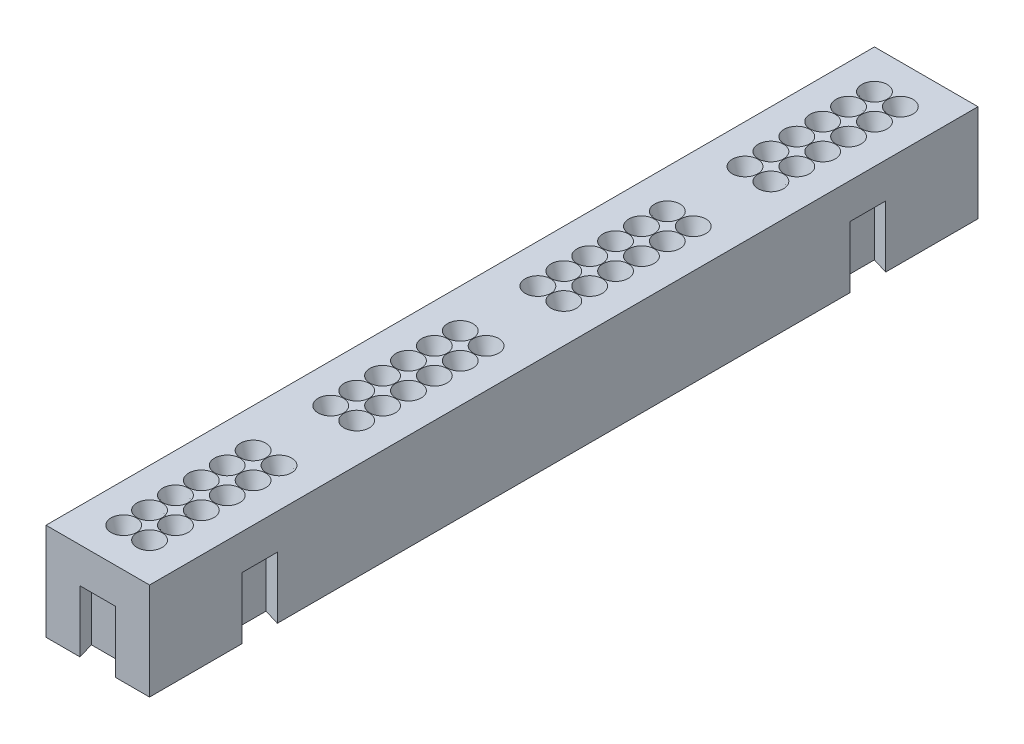
SolidWorks part; units mm, degrees
ref_plane "Front Plane" through (0, 0, 0) normal (0, 0, 1) x (1, 0, 0)
ref_plane "Top Plane" through (0, 0, 0) normal (0, 1, 0) x (1, 0, 0)
ref_plane "Right Plane" through (0, 0, 0) normal (1, 0, 0) x (0, 0, -1)
sketch "Sketch1" plane through (0, 0, 0) normal (0, 1, 0) x (1, 0, 0)
  line L0 (-5.08, -40.64) -> (5.08, 40.64) construction
  line L1 (-5.08, 40.64) -> (5.08, 40.64)
  line L2 (-5.08, 40.64) -> (-5.08, -40.64)
  line L3 (-5.08, -40.64) -> (5.08, -40.64)
  line L4 (5.08, 40.64) -> (5.08, -40.64)
  dimension "D1" = 81.28
  dimension "D2" = 10.16
extrude "Extrude1" add sketch "Sketch1" along normal blind 9.525
sketch "Sketch4" plane through (0, 0, 0) normal (0, -1, 0) x (1, 0, 0)
  line L0 (5.08, -29.845) -> (-5.08, -29.845) construction
  line L1 (5.08, 40.64) -> (5.08, -40.64) construction
  line L2 (-5.08, -40.64) -> (-5.08, 40.64) construction
  line L3 (0, -40.64) -> (0, 40.64) construction
  line L4 (5.08, 29.845) -> (-5.08, 29.845) construction
  line L5 (5.08, -40.64) -> (-5.08, -40.64) construction
  line L6 (-5.08, 40.64) -> (5.08, 40.64) construction
  line L7 (5.08, 29.845) -> (-5.08, -29.845) construction
  dimension "D1" = 59.69
sketch "Sketch3" plane through (0, 0, 0) normal (0, -1, 0) x (1, 0, 0)
  line L0 (5.08, -31.5849) -> (3.4925, -32.0675)
  line L1 (5.08, 40.64) -> (5.08, -40.64) construction
  line L2 (3.4925, -32.0675) -> (3.4925, -27.6225)
  line L3 (3.4925, -27.6225) -> (5.08, -28.1051)
  line L4 (5.08, -28.1051) -> (5.08, -31.5849)
  line L5 (5.08, 28.1051) -> (3.4925, 27.6225)
  line L6 (3.4925, 27.6225) -> (3.4925, 32.0675)
  line L7 (3.4925, 32.0675) -> (5.08, 31.5849)
  line L8 (5.08, 31.5849) -> (5.08, 28.1051)
  line L9 (5.08, -29.845) -> (-5.08, -29.845) construction
  line L10 (5.08, 29.845) -> (-5.08, 29.845) construction
  line L11 (1.7399, 40.64) -> (-1.7399, 40.64)
  line L12 (-5.08, 40.64) -> (5.08, 40.64) construction
  line L13 (-1.7399, 40.64) -> (-2.2225, 39.0525)
  line L14 (-2.2225, 39.0525) -> (2.2225, 39.0525)
  line L15 (2.2225, 39.0525) -> (1.7399, 40.64)
  line L18 (0, -40.64) -> (0, 40.64) construction
  point P8 (3.4925, -29.845)
  point P15 (3.4925, 29.845)
  point P22 (0, 39.0525)
  dimension "D1" = 4.445
  dimension "D2" = 3.4798
  dimension "D3" = 1.5875
  dimension "D4" = 1.5875
extrude "Extrude3" cut sketch "Sketch3" against normal blind 6.0452
sketch "Sketch5" plane through (0, 6.0452, 0) normal (0, -1, 0) x (1, 0, 0)
  line L0 (-5.08, -31.5849) -> (-6.6675, -32.0675)
  line L1 (-6.6675, -32.0675) -> (-6.6675, -27.6225)
  line L2 (-6.6675, -27.6225) -> (-5.08, -28.1051)
  line L3 (-5.08, -28.1051) -> (-5.08, -31.5849)
  line L4 (-5.08, 28.1051) -> (-6.6675, 27.6225)
  line L5 (-6.6675, 27.6225) -> (-6.6675, 32.0675)
  line L6 (-6.6675, 32.0675) -> (-5.08, 31.5849)
  line L7 (-5.08, 31.5849) -> (-5.08, 28.1051)
  line L8 (5.08, -31.5849) -> (5.08, -28.1051) construction
  line L9 (3.4925, -27.6225) -> (3.4925, -32.0675) construction
  line L10 (-5.08, 29.845) -> (-6.6675, 29.845) construction
  line L11 (-6.6675, -29.845) -> (-5.08, -29.845) construction
  line L13 (3.4925, -29.845) -> (5.08, -29.845) construction
  line L14 (1.7399, -40.64) -> (-1.7399, -40.64)
  line L15 (-1.7399, -40.64) -> (-2.2225, -42.2275)
  line L16 (-2.2225, -42.2275) -> (2.2225, -42.2275)
  line L17 (2.2225, -42.2275) -> (1.7399, -40.64)
  line L18 (0, -42.2275) -> (0, -40.64) construction
  point P22 (0, -42.2275)
extrude "Extrude4" add sketch "Sketch5" along normal blind 5.08
hole_wizard "Hole1" positions "Sketch7" profile "Sketch6" legacy
sketch "Sketch7" plane through (0, 9.525, 0) normal (0, 1, 0) x (-1, 0, 0)
  line L0 (5.08, -40.64) -> (5.08, 40.64) construction
  line L1 (5.08, 40.64) -> (-5.08, 40.64) construction
  point P0 (1.27, 36.83)
  dimension "D1" = 3.81
  dimension "D2" = 3.81
sketch "Sketch6" plane through (-1.27, 9.525, 36.83) normal (1, 0, 0) x (0, 0, 1)
  line L0 (0, 0) -> (0, 8.382)
  line L1 (0, 8.382) -> (0.381, 8.382)
  line L2 (0.381, 8.382) -> (0.381, 2.3727)
  line L3 (0.381, 2.3727) -> (1.2446, 0)
  line L4 (1.2446, 0) -> (0, 0)
  line L5 (0, -6.4453) -> (0, 115.525) construction
  line L6 (-0.381, 2.3727) -> (-1.2446, 0) construction
  dimension "Diameter" = 0.762
  dimension "Depth" = 8.382
  dimension "C-Sink Angle" = 40
  dimension "C-Sink Diameter" = 2.4892
pattern_linear "LPattern2" count 2 spacing 2.54 along (1, 0, 0) count 6 spacing 2.54 along (0, 0, -1) of "Hole1"
pattern_linear "LPattern3" count 4 spacing 20.32 along (0, 0, -1) of "LPattern2", "Hole1"
